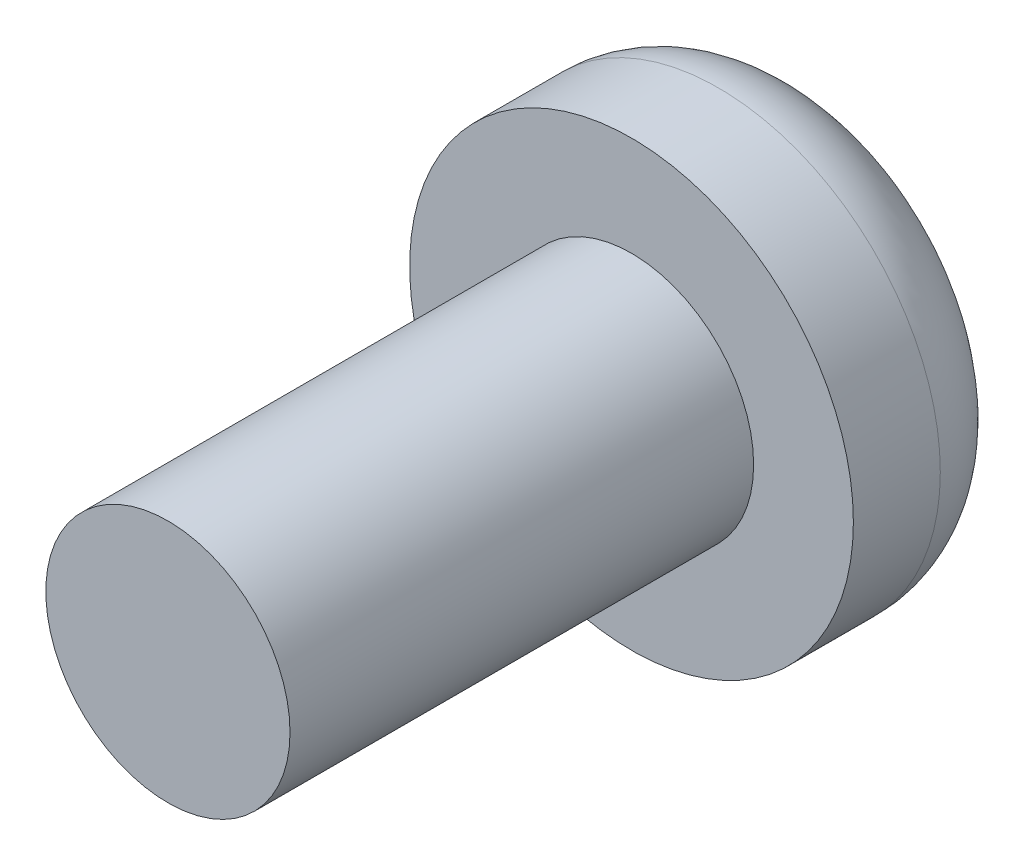
SolidWorks part; units mm, degrees
material "Acero aleado"
ref_plane "Alzado" through (0, 0, 0) normal (0, 0, 1) x (1, 0, 0)
ref_plane "Planta" through (0, 0, 0) normal (0, 1, 0) x (1, 0, 0)
ref_plane "Vista lateral" through (0, 0, 0) normal (1, 0, 0) x (0, 0, -1)
sketch "Croquis1" plane through (0, 0, 0) normal (0, 0, 1) x (1, 0, 0)
  circle A0 centre (0, 0) radius 1.475
  dimension "D1" = 2.95
extrude "Saliente-Extruir1" add sketch "Croquis1" along normal blind 5.6
sketch "Croquis2" plane through (0, 0, 0) normal (0, 0, -1) x (-1, 0, 0)
  circle A0 centre (0, 0) radius 2.68
  dimension "D1" = 5.36
extrude "Saliente-Extruir2" add sketch "Croquis2" along normal blind 2.15
sketch "Croquis3" plane through (0, 0, -2.15) normal (0, 0, -1) x (-1, 0, 0)
  line L1 (0, -1.4197) -> (1.2295, -0.7098)
  line L2 (1.2295, -0.7098) -> (1.2295, 0.7098)
  line L3 (1.2295, 0.7098) -> (0, 1.4197)
  line L4 (0, 1.4197) -> (-1.2295, 0.7098)
  line L5 (-1.2295, 0.7098) -> (-1.2295, -0.7098)
  line L6 (-1.2295, -0.7098) -> (0, -1.4197)
  circle A0 centre (0, 0) radius 1.2295 construction
extrude "Cortar-Extruir1" cut sketch "Croquis3" against normal blind 1.5
fillet "Redondeo1" radius 1.1 1 edges at (-2.68, 0, -2.15)
